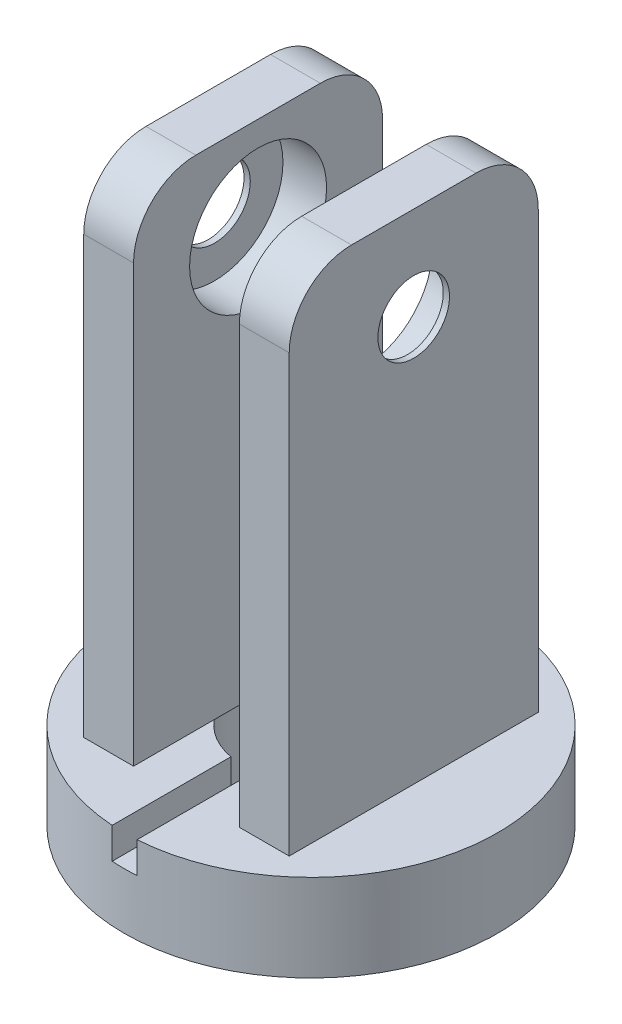
SolidWorks part; units mm, degrees
material "6061 Alloy"
ref_plane "Front Plane" through (0, 0, 0) normal (0, 0, 1) x (1, 0, 0)
ref_plane "Top Plane" through (0, 0, 0) normal (0, 1, 0) x (1, 0, 0)
ref_plane "Right Plane" through (0, 0, 0) normal (1, 0, 0) x (0, 0, -1)
sketch "Sketch1" plane through (0, 0, 0) normal (0, 1, 0) x (1, 0, 0)
  circle A0 centre (0, 0) radius 30
  dimension "D1" = 60
extrude "Boss-Extrude1" add sketch "Sketch1" along normal blind 14
sketch "Sketch2" plane through (0, 0, 0) normal (0, -1, 0) x (1, 0, 0)
  circle A0 centre (0, 0) radius 11.05
  dimension "D1" = 22.1
extrude "Cut-Extrude1" cut sketch "Sketch2" against normal through all
sketch "Sketch5" plane through (0, 14, 0) normal (0, 1, 0) x (1, 0, 0)
  line L0 (0, 0) -> (-8.5, 0) construction
  line L1 (0, 0) -> (8.5, 0) construction
  line L2 (-8.5, -20) -> (-8.5, 20)
  line L3 (-8.5, 20) -> (-16.5, 20)
  line L4 (-16.5, 20) -> (-16.5, -20)
  line L5 (-16.5, -20) -> (-8.5, -20)
  line L7 (16.5, -20) -> (16.5, 20)
  line L8 (16.5, 20) -> (8.5, 20)
  line L9 (8.5, 20) -> (8.5, -20)
  line L10 (8.5, -20) -> (16.5, -20)
  dimension "D1" = 8.5
  dimension "D2" = 8.5
  dimension "D3" = 8
  dimension "D4" = 20
  dimension "D5" = 20
  dimension "D6" = 0
  dimension "D7" = 8
  dimension "D8" = 20
  dimension "D9" = 20
extrude "Boss-Extrude2" add sketch "Sketch5" along normal blind 80
fillet "Fillet1" radius 10 4 edges at (-12.5, 94, -20) (12.5, 94, -20) (12.5, 94, 20) (-12.5, 94, 20)
sketch "Sketch8" plane through (0, 14, 0) normal (0, 1, 0) x (1, 0, 0)
  line L0 (0, 0) -> (2, 0) construction
  line L1 (0, 0) -> (-2, 0) construction
  line L2 (2, 29.9333) -> (2, -29.9333)
  line L3 (-2, 29.9333) -> (-2, -29.9333)
  circle A0 centre (0, 0) radius 30 construction
  arc A1 (-2, -29.9333) -> (2, -29.9333) centre (0, 0) ccw
  arc A2 (2, 29.9333) -> (-2, 29.9333) centre (0, 0) ccw
  dimension "D1" = 2
  dimension "D2" = 2
extrude "Cut-Extrude4" cut sketch "Sketch8" against normal blind 5
sketch "Sketch12" plane through (0, 0, 0) normal (1, 0, 0) x (0, 0, -1)
  line L0 (-20, 84) -> (-20, 14) construction
  line L1 (-10, 94) -> (10, 94) construction
  circle A0 centre (0, 79) radius 11
  dimension "D1" = 22
  dimension "D2" = 20
  dimension "D3" = 15
extrude "Cut-Extrude5" cut sketch "Sketch12" against normal offset from surface 1 and the other way offset from surface (15.5 mm away) 1 up to face at (-16.5, 64.6904, 0) other way up to face at (16.5, 64.6904, 0)
sketch "Sketch13" plane through (-16.5, 0, 0) normal (-1, 0, 0) x (0, 0, 1)
  line L0 (-10, 94) -> (10, 94) construction
  line L1 (-20, 84) -> (-20, 14) construction
  circle A0 centre (0, 79) radius 5.75
  dimension "D1" = 11.5
  dimension "D2" = 15
  dimension "D3" = 20
extrude "Cut-Extrude6" cut sketch "Sketch13" against normal up to surface (33 mm away) up to face at (16.5, 64.6904, 0)
